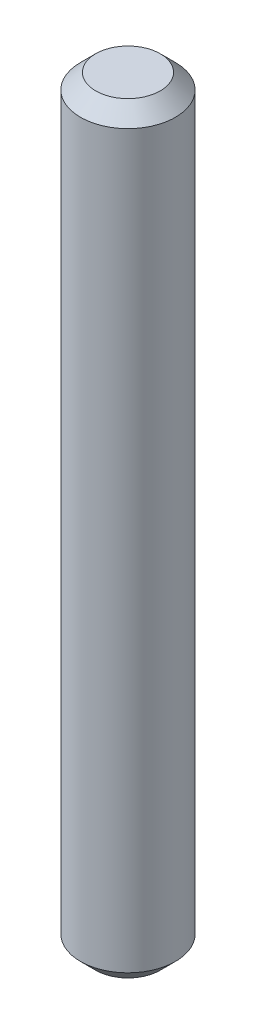
SolidWorks part; units mm, degrees
ref_plane "Front Plane" through (0, 0, 0) normal (0, 0, 1) x (1, 0, 0)
ref_plane "Top Plane" through (0, 0, 0) normal (0, 1, 0) x (1, 0, 0)
ref_plane "Right Plane" through (0, 0, 0) normal (1, 0, 0) x (0, 0, -1)
ref_plane "Plane1" through (0, 0, 0) normal (0, 0, -1) x (-1, 0, 0)
sketch "Sketch1" plane through (0, 0, 0) normal (0, 0, -1) x (-1, 0, 0)
  line L0 (-1.0757, 0) -> (0, 0)
  line L1 (0, 0) -> (0, 25.4)
  line L2 (0, 25.4) -> (-1.0757, 25.4)
  line L3 (-1.0757, 25.4) -> (-1.5837, 24.892)
  line L4 (-1.5837, 24.892) -> (-1.5837, 0.508)
  line L5 (-1.5837, 0.508) -> (-1.0757, 0)
  line L6 (0, 0) -> (0, 25.4) construction
revolve "Revolve1" add sketch "Sketch1" angle 360 about L6
